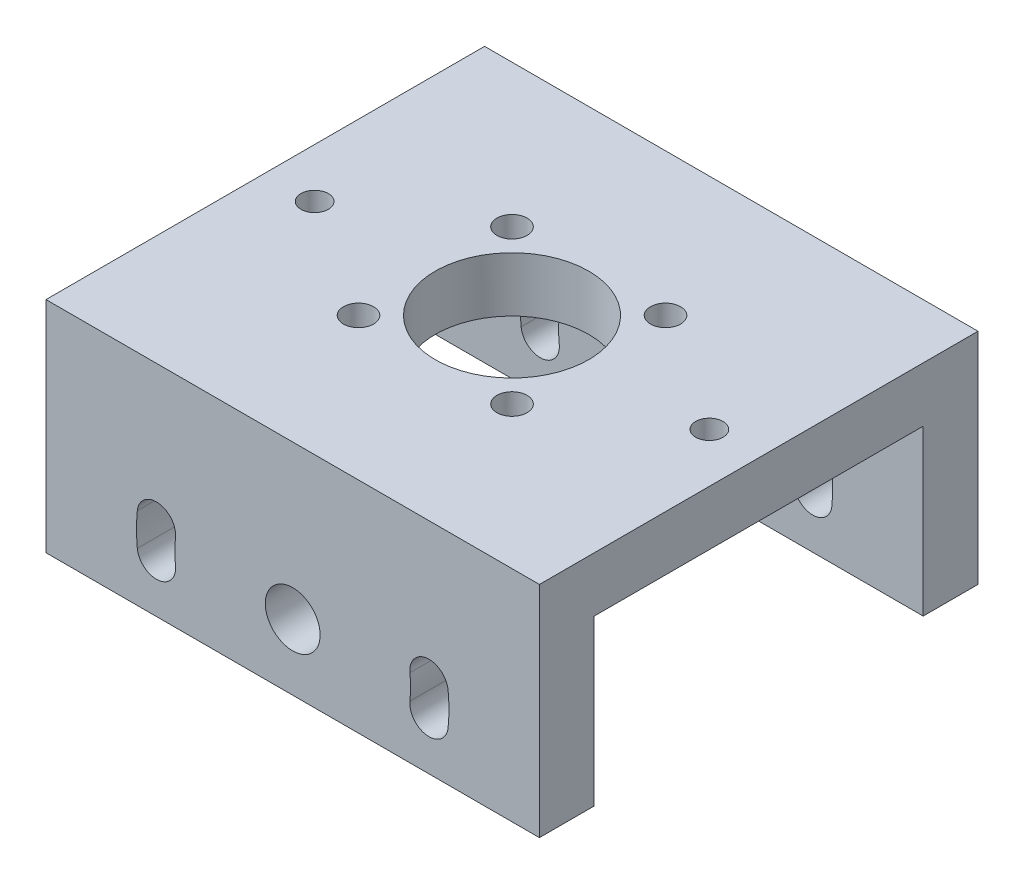
SolidWorks part; units mm, degrees
material "6061"
ref_plane "前视" through (0, 0, 0) normal (0, 0, 1) x (1, 0, 0)
ref_plane "上视" through (0, 0, 0) normal (0, 1, 0) x (1, 0, 0)
ref_plane "右视" through (0, 0, 0) normal (1, 0, 0) x (0, 0, -1)
sketch "草图1" plane through (0, 0, 0) normal (0, 1, 0) x (1, 0, 0)
  line L1 (-45, -40) -> (45, -40)
  line L2 (-45, -40) -> (-45, 40)
  line L3 (-45, 40) -> (45, 40)
  line L4 (45, -40) -> (45, 40)
  line L5 (-45, -40) -> (45, 40) construction
  line L6 (-45, 40) -> (45, -40) construction
  point P0 (0, 0)
  dimension "D1" = 90
  dimension "D2" = 80
extrude "凸台-拉伸1" add sketch "草图1" along normal blind 40
sketch "草图10" plane through (45, 0, 0) normal (1, 0, 0) x (0, 0, -1)
  line L0 (0, 40) -> (0, 0) construction
  line L1 (-40, 40) -> (40, 40) construction
  line L2 (-40, 0) -> (40, 0) construction
  line L3 (-30, 30) -> (30, 30)
  line L4 (-30, 30) -> (-30, 0)
  line L5 (-30, 0) -> (30, 0)
  line L6 (30, 30) -> (30, 0)
  line L7 (-30, 30) -> (30, 0) construction
  line L8 (-30, 0) -> (30, 30) construction
  line L9 (40, 40) -> (40, 0) construction
  point P5 (0, 15)
  dimension "D1" = 10
  dimension "D2" = 10
extrude "切除-拉伸1" cut sketch "草图10" against normal through all
hole_wizard "孔2" positions "草图12" profile "草图11" legacy end condition through all
sketch "草图12" plane through (0, 0, 40) normal (0, 0, 1) x (1, 0, 0)
  line L0 (0, 40) -> (0, 12) construction
  line L1 (-45, 40) -> (45, 40) construction
  line L2 (-45, 0) -> (45, 0) construction
  point P0 (0, 12)
  dimension "D1" = 12
sketch "草图11" plane through (0, 12, 40) normal (1, 0, 0) x (0, -1, 0)
  line L0 (0, 0) -> (0, 80)
  line L1 (0, 80) -> (5, 80)
  line L2 (5, 80) -> (5, 0)
  line L3 (5, 0) -> (0, 0)
  line L4 (0, 110) -> (0, -10) construction
  dimension "直径" = 10
  dimension "深度" = 80
sketch "草图13" plane through (0, 0, 40) normal (0, 0, 1) x (1, 0, 0)
  line L0 (0, 12) -> (-25, 12) construction
  line L1 (0, 12) -> (0, 29.797) construction
  line L2 (-28.3439, 14.9791) -> (0, 12) construction
  line L3 (-28.3439, 9.0209) -> (0, 12) construction
  circle A0 centre (0, 12) radius 25 construction
  arc A1 (-28.3439, 14.9791) -> (-28.3439, 9.0209) centre (0, 12) ccw
  arc A2 (-21.3822, 14.2474) -> (-21.3822, 9.7526) centre (0, 12) ccw
  arc A3 (-28.3439, 14.9791) -> (-21.3822, 14.2474) centre (-24.863, 14.6132) cw
  arc A4 (-21.3822, 9.7526) -> (-28.3439, 9.0209) centre (-24.863, 9.3868) cw
  arc A5 (21.3822, 9.7526) -> (28.3439, 9.0209) centre (24.863, 9.3868) ccw
  arc A6 (28.3439, 14.9791) -> (21.3822, 14.2474) centre (24.863, 14.6132) ccw
  arc A7 (21.3822, 14.2474) -> (21.3822, 9.7526) centre (0, 12) cw
  arc A8 (28.3439, 14.9791) -> (28.3439, 9.0209) centre (0, 12) cw
  dimension "D1" = 3.5
  dimension "D2" = 50
  dimension "D3" = 6
extrude "切除-拉伸2" cut sketch "草图13" against normal through all
hole_wizard "打孔尺寸根据内六角圆柱头螺钉的类型1" positions "草图3" profile "草图2" counterbore size "M5" standard "Gb" end condition through all
sketch "草图3" plane through (-40.1486, 30, -46.4685) normal (0, -1, 0) x (-1, 0, 0)
  line L0 (-40.1486, -86.4685) -> (-40.1486, -46.4685) construction
  line L1 (4.8514, -86.4685) -> (-85.1486, -86.4685) construction
  line L2 (-40.1486, -46.4685) -> (-85.1486, -46.4685) construction
  line L4 (-85.1486, -16.4685) -> (-85.1486, -76.4685) construction
  point P0 (-26.1486, -60.4685)
  point P12 (-54.1486, -60.4685)
  point P13 (-54.1486, -32.4685)
  point P14 (-26.1486, -32.4685)
  dimension "D1" = 28
  dimension "D2" = 28
sketch "草图2" plane through (-14, 30, 14) normal (1, 0, 0) x (0, 0, -1)
  line L0 (0, 0) -> (0, 10)
  line L1 (0, 10) -> (2.75, 10)
  line L3 (2.75, 10) -> (2.75, 5.7)
  line L4 (2.75, 5.7) -> (5, 5.7)
  line L5 (5, 5.7) -> (5, 0)
  line L7 (5, 0) -> (0, 0)
  line L11 (0, -6.35) -> (0, 107.95) construction
  dimension "通孔孔直径" = 5.5
  dimension "通孔孔深度" = 10
  dimension "柱形沉头孔直径" = 10
  dimension "柱形沉头孔深度" = 5.7
hole_wizard "孔1" positions "草图5" profile "草图4" legacy end condition through all
sketch "草图5" plane through (0, 0, 0) normal (0, -1, 0) x (-1, 0, 0)
  point P0 (0, 0)
sketch "草图4" plane through (0, 0, 0) normal (1, 0, 0) x (0, 0, -1)
  line L0 (0, 0) -> (0, 40)
  line L1 (0, 40) -> (14, 40)
  line L2 (14, 40) -> (14, 0)
  line L3 (14, 0) -> (0, 0)
  line L4 (0, 110) -> (0, -10) construction
  dimension "直径" = 28
  dimension "深度" = 40
hole_wizard "M6 螺纹孔1" positions "草图9" profile "草图8" tap size "M6" standard "Gb" end condition through all
sketch "草图9" plane through (0, 40, 0) normal (0, 1, 0) x (1, 0, 0)
  line L0 (0, 0) -> (0, 28.6446) construction
  point P0 (-36, 0)
  point P7 (36, 0)
  dimension "D1" = 72
sketch "草图8" plane through (-36, 40, 0) normal (1, 0, 0) x (0, 0, 1)
  line L0 (0, 0) -> (0, 40)
  line L1 (0, 40) -> (2.5, 40)
  line L2 (2.5, 40) -> (2.5, 0)
  line L5 (2.5, 0) -> (0, 0)
  line L11 (0, -6.35) -> (0, 107.95) construction
  dimension "通孔螺纹孔钻头直径" = 5
  dimension "通孔螺纹孔钻头深度" = 40
cosmetic thread "孔螺蚊线1" parameters "D2"=6
cosmetic thread "孔螺蚊线2" parameters "D2"=6
